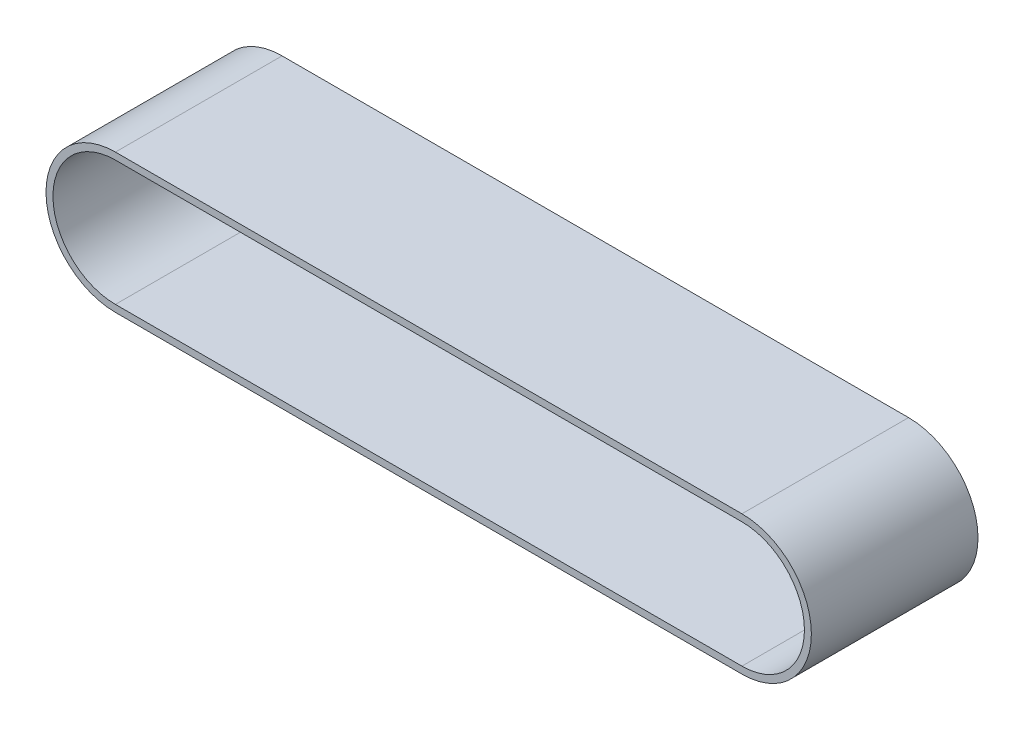
SolidWorks part; units mm, degrees
material "SBR"
ref_plane "Front Plane" through (0, 0, 0) normal (0, 0, 1) x (1, 0, 0)
ref_plane "Top Plane" through (0, 0, 0) normal (0, 1, 0) x (1, 0, 0)
ref_plane "Right Plane" through (0, 0, 0) normal (1, 0, 0) x (0, 0, -1)
sketch "Sketch2" plane through (0, 0, 0) normal (0, 0, 1) x (1, 0, 0)
  line L0 (-286.5, 0) -> (286.5, 0) construction
  line L1 (-286.5, 63.5) -> (286.5, 63.5)
  line L2 (-286.5, -63.5) -> (286.5, -63.5)
  line L3 (-286.5, 0) -> (286.5, 0) construction
  line L4 (-286.5, 57.15) -> (286.5, 57.15)
  line L5 (-286.5, -57.15) -> (286.5, -57.15)
  arc A0 (-286.5, 63.5) -> (-286.5, -63.5) centre (-286.5, 0) ccw
  arc A1 (286.5, -63.5) -> (286.5, 63.5) centre (286.5, 0) ccw
  arc A2 (-286.5, 57.15) -> (-286.5, -57.15) centre (-286.5, 0) ccw
  arc A3 (286.5, -57.15) -> (286.5, 57.15) centre (286.5, 0) ccw
  point P3 (0, 0)
  point P10 (0, 0)
  dimension "D1" = 63.5
  dimension "D4" = 57.15
  dimension "D2" = 286.5
  dimension "D3" = 286.5
extrude "Boss-Extrude2" add sketch "Sketch2" along normal blind 152.4
